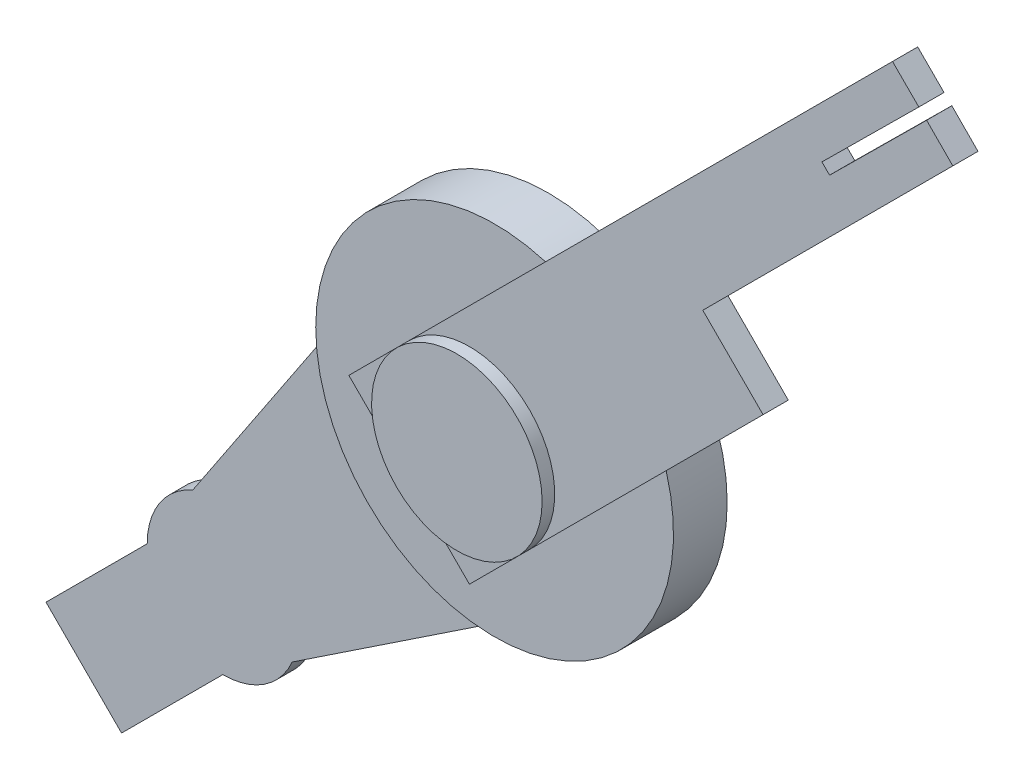
SolidWorks part; units mm, degrees
ref_plane "Front Plane" through (0, 0, 0) normal (0, 0, 1) x (1, 0, 0)
ref_plane "Top Plane" through (0, 0, 0) normal (0, 1, 0) x (1, 0, 0)
ref_plane "Right Plane" through (0, 0, 0) normal (1, 0, 0) x (0, 0, -1)
sketch "Sketch2" plane through (0, 0, 0) normal (0, 0, 1) x (1, 0, 0)
  line L0 (-7.9375, 0) -> (-14.9775, -10.5702)
  line L1 (0, -7.9375) -> (-10.5702, -14.9775)
  line L2 (-17.001, -13.6482) -> (-13.6482, -17.001)
  line L3 (-13.6482, -17.001) -> (-18.1383, -21.4911)
  line L6 (-18.1383, -21.4911) -> (-21.4911, -18.1383)
  line L7 (-21.4911, -18.1383) -> (-17.001, -13.6482)
  circle A0 centre (0, 0) radius 7.9375
  arc A1 (-14.9775, -10.5702) -> (-10.5702, -14.9775) centre (-13.6482, -13.6482) ccw
  dimension "D1" = 15.875
  dimension "D5" = 12.7
  dimension "D4" = 12.7
  dimension "D2" = 3.3528
  dimension "D6" = 6.35
  dimension "D3" = 6.35
extrude "Boss-Extrude1" add sketch "Sketch2" along normal blind 0.7937 contours L0 A1 L2 L1 A0 | A1 L7 L6 L3 | A0
sketch "Sketch3" plane through (0, 0, 0.7937) normal (0, 0, 1) x (1, 0, 0)
  circle A0 centre (0, 0) radius 7.9375
extrude "Boss-Extrude2" add sketch "Sketch3" along normal blind 1.5875
sketch "Sketch4" plane through (0, 0, 2.3812) normal (0, 0, 1) x (1, 0, 0)
  line L0 (-5.35, 0) -> (0, -5.35)
  line L1 (1.3097, 0) -> (-1.3097, 0) construction
  line L2 (0, -1.3097) -> (0, 1.3097) construction
  line L3 (0, -5.35) -> (13.0278, 7.6778)
  line L4 (13.0278, 7.6778) -> (7.6778, 13.0278)
  line L5 (7.6778, 13.0278) -> (-5.35, 0)
  line L6 (10.3528, 10.3528) -> (16.9546, 16.9546)
  line L7 (16.9546, 16.9546) -> (14.2797, 19.6296)
  line L8 (14.2797, 19.6296) -> (7.6778, 13.0278)
  line L9 (14.2797, 19.6296) -> (18.7698, 24.1198)
  line L10 (18.7698, 24.1198) -> (19.9372, 22.9523)
  line L11 (19.9372, 22.9523) -> (15.6394, 18.6959)
  line L12 (15.6394, 18.6959) -> (15.9779, 18.3542)
  line L13 (15.9779, 18.3542) -> (20.283, 22.6178)
  line L14 (20.283, 22.6178) -> (21.4448, 21.4448)
  line L15 (21.4448, 21.4448) -> (16.9546, 16.9546)
  circle M13 centre (0, 0) radius 7.9375
  dimension "D1" = 7.566
  dimension "D2" = 45
  dimension "D3" = 1.651
  dimension "D4" = 1.651
  dimension "D6" = 6.35
  dimension "D7" = 6.35
extrude "Boss-Extrude3" add sketch "Sketch4" along normal blind 1.1176 contours L4 L5 L3 M13 | L5 L0 L3 M13 | L7 L8 L4 L6 | L15 L14 L13 L12 L11 L10 L9 L7
sketch "Sketch5" plane through (0, 0, 3.4988) normal (0, 0, 1) x (1, 0, 0)
  circle A0 centre (0, 0) radius 3.783
extrude "Boss-Extrude4" add sketch "Sketch5" along normal blind 0.5588
sketch "Sketch7" plane through (0, 0, 0) normal (0, 0, -1) x (-1, 0, 0)
  circle A0 centre (0, 0) radius 1.905
  dimension "D1" = 3.81
extrude "Boss-Extrude5" add sketch "Sketch7" along normal blind 1.5875
equation "\"0.62r5\"=0.0209154"
